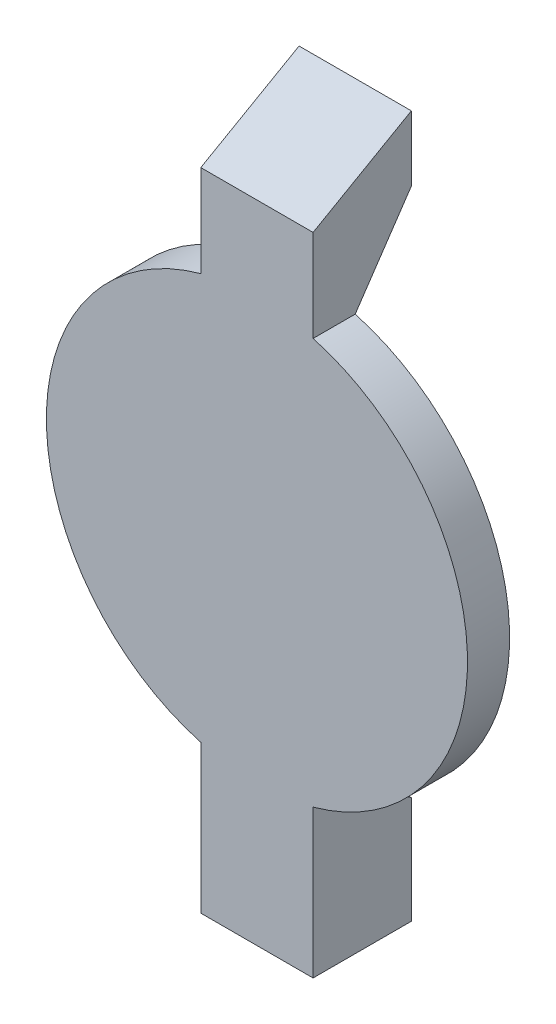
SolidWorks part; units mm, degrees
ref_plane "Alzado" through (0, 0, 0) normal (0, 0, 1) x (1, 0, 0)
ref_plane "Planta" through (0, 0, 0) normal (0, 1, 0) x (1, 0, 0)
ref_plane "Vista lateral" through (0, 0, 0) normal (1, 0, 0) x (0, 0, -1)
sketch "Croquis1" plane through (0, 0, 0) normal (0, 0, 1) x (1, 0, 0)
  line L0 (-50.0645, 3.5161) -> (-58.0645, 3.5161) construction
  line L1 (-58.0645, 28.5161) -> (-50.0645, 28.5161)
  line L2 (-58.0645, 28.5161) -> (-58.0645, 17.973)
  line L3 (-58.0645, -21.4839) -> (-50.0645, -21.4839)
  line L4 (-58.0645, -10.9407) -> (-58.0645, -21.4839)
  line L5 (-50.0645, 28.5161) -> (-50.0645, 17.973)
  line L6 (-50.0645, -10.9407) -> (-50.0645, -21.4839)
  arc A1 (-58.0645, 17.973) -> (-58.0645, -10.9407) centre (-54.0645, 3.5161) ccw
  arc A2 (-50.0645, 17.973) -> (-50.0645, -10.9407) centre (-54.0645, 3.5161) cw
  dimension "D1" = 8
  dimension "D2" = 50
extrude "Saliente-Extruir1" add sketch "Croquis1" along normal blind 7
sketch "Croquis2" plane through (0, -21.4839, 0) normal (0, -1, 0) x (1, 0, 0)
  circle A0 centre (-54.0645, 3.5) radius 2.4
extrude "Cortar-Extruir1" cut sketch "Croquis2" against normal blind 5
sketch "Croquis3" plane through (-58.0645, 0, 0) normal (-1, 0, 0) x (0, 0, 1)
  line L0 (7, 28.5161) -> (7, 24.5161) construction
  line L1 (7, 28.5161) -> (7, 17.973) construction
  line L2 (7, 24.5161) -> (0, 28.5161)
  line L3 (0, 28.5161) -> (7, 28.5161)
  line L4 (7, 28.5161) -> (7, 24.5161)
extrude "Cortar-Extruir2" cut sketch "Croquis3" against normal up to vertex (8 mm away)
ref_plane "Plano1" through (-69.0645, 0, 0) normal (-1, 0, 0) x (0, 0, 1)
sketch "Croquis4" plane through (-69.0645, 0, 0) normal (-1, 0, 0) x (0, 0, 1)
  line L1 (0, 23.8721) -> (4, 23.8721)
  line L2 (0, 23.8721) -> (0, -13.8562)
  line L3 (0, -13.8562) -> (4, -13.8562)
  line L4 (4, 23.8721) -> (4, -13.8562)
  dimension "D1" = 4
extrude "Cortar-Extruir3" cut sketch "Croquis4" against normal blind 40
sketch "Croquis5" plane through (-58.0645, 0, 0) normal (-1, 0, 0) x (0, 0, 1)
  line L0 (0, 23.8721) -> (4, 17.973)
  line L1 (4, 17.973) -> (4, 23.8721)
  line L2 (4, 23.8721) -> (0, 23.8721)
  line L3 (0, -13.8562) -> (4, -10.9407)
  line L4 (4, -10.9407) -> (4, -13.8562)
  line L5 (4, -13.8562) -> (0, -13.8562)
extrude "Saliente-Extruir2" add sketch "Croquis5" against normal up to vertex (8 mm away)
